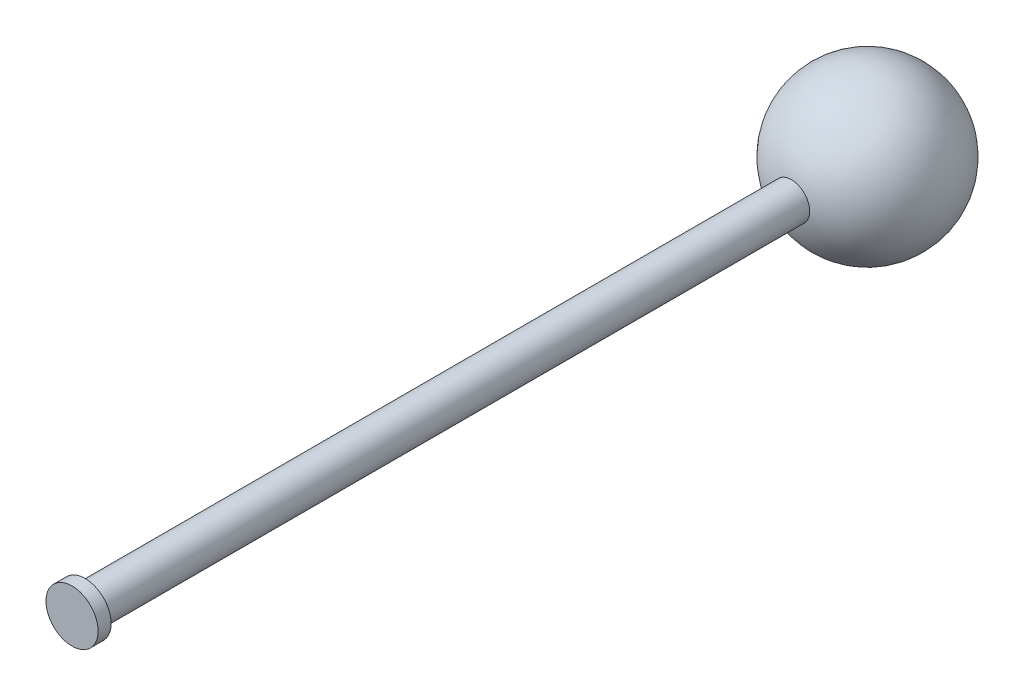
SolidWorks part; units mm, degrees
ref_plane "Ön Düzlem" through (0, 0, 0) normal (0, 0, 1) x (1, 0, 0)
ref_plane "Üst Düzlem" through (0, 0, 0) normal (0, 1, 0) x (1, 0, 0)
ref_plane "Sağ Düzlem" through (0, 0, 0) normal (1, 0, 0) x (0, 0, -1)
sketch "Sketch1" plane through (0, 0, 0) normal (0, 0, 1) x (1, 0, 0)
  line L0 (0, 3) -> (0, -3)
  arc A0 (0, -3) -> (0, 3) centre (0, 0) ccw
  dimension "D1" = 6
revolve "Revolve1" add sketch "Sketch1" angle 360 about L0
sketch "Sketch2" plane through (0, 0, 0) normal (0, 0, 1) x (1, 0, 0)
  circle A0 centre (0, 0) radius 0.7
  dimension "D1" = 1.4
extrude "Boss-Extrude2" add sketch "Sketch2" along normal blind 30
sketch "Sketch3" plane through (0, 0, 30) normal (0, 0, 1) x (1, 0, 0)
  circle A0 centre (0, 0) radius 1
  dimension "D1" = 2
extrude "Boss-Extrude3" add sketch "Sketch3" along normal blind 0.5
